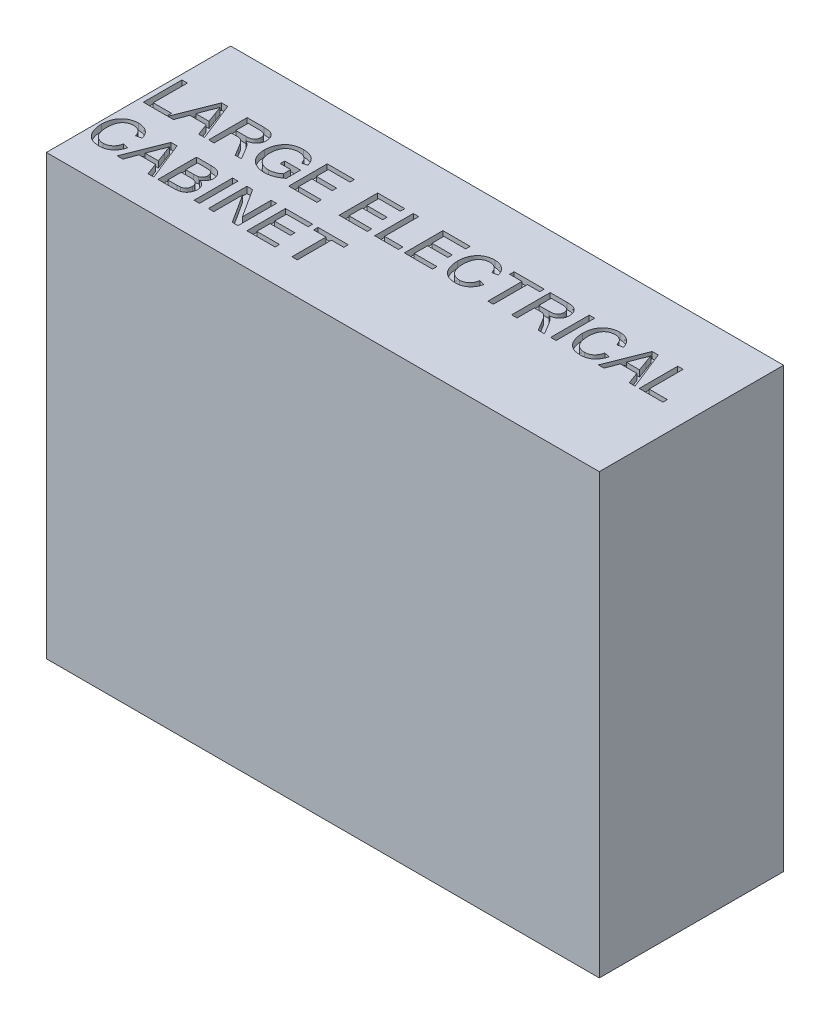
SolidWorks part; units mm, degrees
ref_plane "Front" through (0, 0, 0) normal (0, 0, 1) x (1, 0, 0)
ref_plane "Top" through (0, 0, 0) normal (0, 1, 0) x (1, 0, 0)
ref_plane "Right" through (0, 0, 0) normal (1, 0, 0) x (0, 0, -1)
sketch "Sketch1" plane through (0, 0, 0) normal (0, 1, 0) x (1, 0, 0)
  line L1 (-1104.9, 368.3) -> (1104.9, 368.3)
  line L2 (-1104.9, 368.3) -> (-1104.9, -368.3)
  line L3 (-1104.9, -368.3) -> (1104.9, -368.3)
  line L4 (1104.9, 368.3) -> (1104.9, -368.3)
  line L5 (-1104.9, 368.3) -> (1104.9, -368.3) construction
  line L6 (-1104.9, -368.3) -> (1104.9, 368.3) construction
  point P0 (0, 0)
  dimension "D1" = 2209.8
  dimension "D2" = 736.6
extrude "Boss-Extrude1" add sketch "Sketch1" along normal blind 1752.6
sketch "Sketch2" plane through (0, 1752.6, 0) normal (0, 1, 0) x (1, 0, 0)
  line L0 (-1102.6964, -0.7599) -> (911.4503, -0.7599) construction
  text T0 "LARGE ELECTRICAL\r\nCABINET" font "Arial" height in points 600
extrude "Cut-Extrude1" cut sketch "Sketch2" against normal blind 25.4
